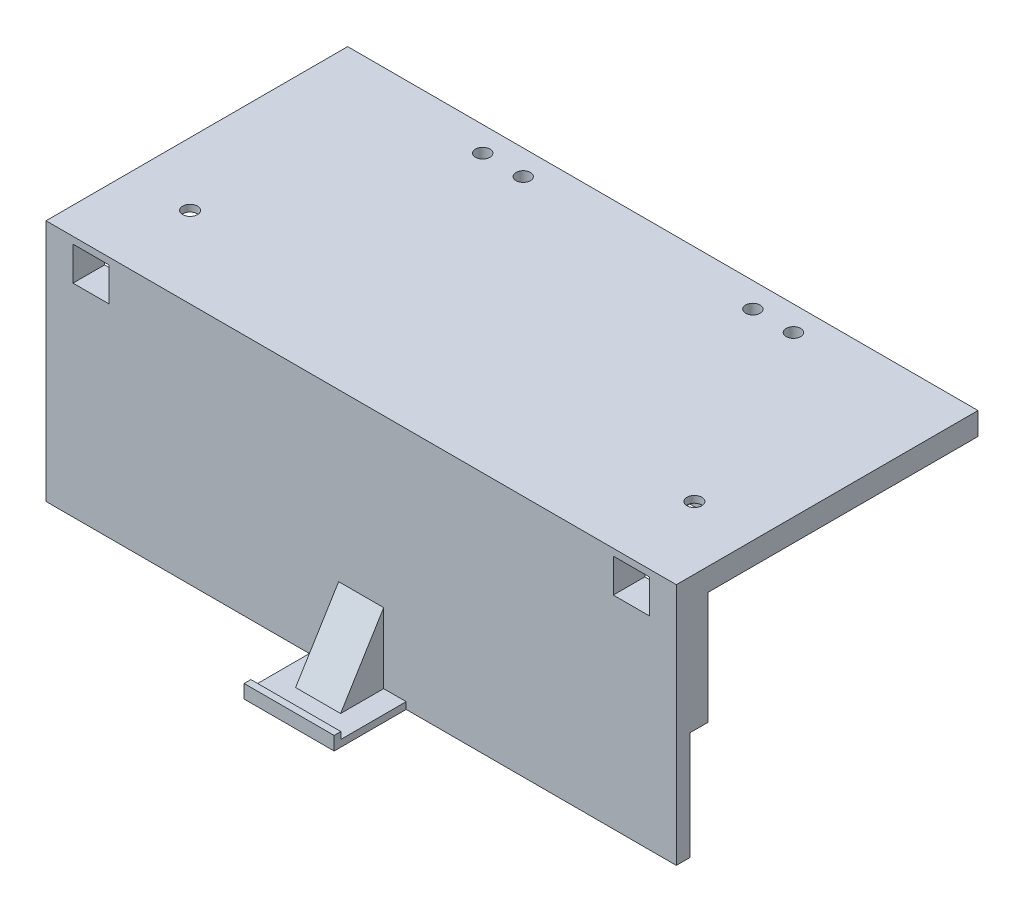
SolidWorks part; units mm, degrees
ref_plane "前视基准面" through (0, 0, 0) normal (0, 0, 1) x (1, 0, 0)
ref_plane "上视基准面" through (0, 0, 0) normal (0, 1, 0) x (1, 0, 0)
ref_plane "右视基准面" through (0, 0, 0) normal (1, 0, 0) x (0, 0, -1)
sketch "草图1" plane through (0, 0, 0) normal (1, 0, 0) x (0, 0, -1)
  line L0 (-15, 27) -> (15, 27)
  line L1 (-15, 27) -> (15, 27) construction
  line L2 (-15, 27) -> (-15, -27) construction
  line L3 (-15, -27) -> (15, -27) construction
  line L4 (15, 27) -> (15, -27) construction
  line L5 (-15, 27) -> (15, -27) construction
  line L6 (-15, -27) -> (15, 27) construction
  line L7 (15, 27) -> (-15, 27) construction
  line L8 (15, 27) -> (15, 17) construction
  line L9 (15, 17) -> (-15, 17) construction
  line L10 (-15, 27) -> (-15, 17) construction
  line L11 (15, 27) -> (-15, 17) construction
  line L12 (15, 17) -> (-15, 27) construction
  line L13 (-15, 17) -> (-12, 17) construction
  line L14 (-15, 17) -> (-15, -27) construction
  line L15 (-15, -27) -> (-12, -27) construction
  line L16 (-12, 17) -> (-12, -27) construction
  line L17 (-15, 17) -> (-12, -27) construction
  line L18 (-15, -27) -> (-12, 17) construction
  line L19 (15, 17) -> (-8, 17) construction
  line L20 (15, 17) -> (15, 27) construction
  line L21 (15, 27) -> (-8, 27) construction
  line L22 (-8, 17) -> (-8, 27) construction
  line L23 (15, 17) -> (-8, 27) construction
  line L24 (15, 27) -> (-8, 17) construction
  line L25 (15, 27) -> (-8, 27) construction
  line L26 (15, 27) -> (15, 22) construction
  line L27 (15, 22) -> (-8, 22) construction
  line L28 (-8, 27) -> (-8, 22) construction
  line L29 (15, 27) -> (-8, 22) construction
  line L30 (15, 22) -> (-8, 27) construction
  line L31 (15, 27) -> (15, 22)
  line L32 (15, 22) -> (-8, 22)
  line L33 (-8, 22) -> (-8, 17)
  line L36 (-12, -27) -> (-15, -27)
  line L37 (-15, -27) -> (-15, 27)
  line L38 (-8, 17) -> (-8, -3)
  line L39 (-8, 17) -> (-12, 17) construction
  line L40 (-8, 17) -> (-8, -3) construction
  line L41 (-8, -3) -> (-12, -3) construction
  line L42 (-12, 17) -> (-12, -3) construction
  line L43 (-10, -3) -> (-10, 17) construction
  line L44 (-8, 7) -> (-12, 7) construction
  line L45 (-8, -3) -> (-12, -3)
  line L46 (-12, -3) -> (-12, -27)
  point P0 (0, 0)
  point P8 (0, 22)
  point P11 (-13.5, -5)
  point P14 (3.5, 22)
  point P17 (3.5, 24.5)
  point P368 (-10, 7)
  dimension "D1" = 54
  dimension "D2" = 30
  dimension "D3" = 10
  dimension "D4" = 3
  dimension "D5" = 23
  dimension "D6" = 20
extrude "凸台-拉伸1" add sketch "草图1" along normal blind 140
sketch "草图2" plane through (0, 27, 0) normal (0, 1, 0) x (1, 0, 0)
  line L1 (0, -15) -> (140, -15) construction
  line L2 (0, -15) -> (0, 15) construction
  line L3 (0, 15) -> (140, 15) construction
  line L4 (140, -15) -> (140, 15) construction
  line L5 (0, -15) -> (140, 15) construction
  line L6 (0, 15) -> (140, -15) construction
  line L7 (0, -15) -> (140, -15) construction
  line L8 (0, -15) -> (0, 3) construction
  line L9 (0, 3) -> (140, 3) construction
  line L10 (140, -15) -> (140, 3) construction
  line L11 (0, -15) -> (140, 3) construction
  line L12 (0, 3) -> (140, -15) construction
  line L13 (14, 3) -> (126, 3) construction
  line L14 (14, 3) -> (14, -15) construction
  line L15 (14, -15) -> (126, -15) construction
  line L16 (126, 3) -> (126, -15) construction
  line L17 (14, 3) -> (126, -15) construction
  line L18 (14, -15) -> (126, 3) construction
  circle A0 centre (14, 3) radius 1.65
  circle A1 centre (126, 3) radius 1.65
  point P4 (70, 0)
  point P9 (70, -6)
  point P10 (70, -6)
  dimension "D1" = 18
  dimension "D2" = 112
extrude "切除-拉伸1" cut sketch "草图2" against normal up to surface (5 mm away) up to face at (70, 22, -3.5)
sketch "草图3" plane through (0, 0, 15) normal (0, 0, 1) x (1, 0, 0)
  line L1 (0, 27) -> (140, 27) construction
  line L2 (0, 27) -> (0, -27) construction
  line L3 (0, -27) -> (140, -27) construction
  line L4 (140, 27) -> (140, -27) construction
  line L5 (0, 27) -> (140, -27) construction
  line L6 (0, -27) -> (140, 27) construction
  line L7 (14, 27) -> (126, 27) construction
  line L8 (14, 27) -> (14, -27) construction
  line L9 (14, -27) -> (126, -27) construction
  line L10 (126, 27) -> (126, -27) construction
  line L11 (14, 27) -> (126, -27) construction
  line L12 (14, -27) -> (126, 27) construction
  line L13 (6, 27) -> (134, 27) construction
  line L14 (6, 27) -> (6, -27) construction
  line L15 (6, -27) -> (134, -27) construction
  line L16 (134, 27) -> (134, -27) construction
  line L17 (6, 27) -> (134, -27) construction
  line L18 (6, -27) -> (134, 27) construction
  line L19 (6, 27) -> (134, 27) construction
  line L20 (6, 27) -> (6, 18) construction
  line L21 (6, 18) -> (134, 18) construction
  line L22 (134, 27) -> (134, 18) construction
  line L23 (6, 27) -> (134, 18) construction
  line L24 (6, 18) -> (134, 27) construction
  line L25 (6, 27) -> (134, 27) construction
  line L26 (6, 27) -> (6, 25.5) construction
  line L27 (6, 25.5) -> (134, 25.5) construction
  line L28 (134, 27) -> (134, 25.5) construction
  line L29 (6, 27) -> (134, 25.5) construction
  line L30 (6, 25.5) -> (134, 27) construction
  line L31 (6, 25.5) -> (14, 25.5)
  line L32 (6, 25.5) -> (6, 18)
  line L33 (6, 18) -> (14, 18)
  line L34 (14, 25.5) -> (14, 18)
  line L35 (6, 25.5) -> (14, 18) construction
  line L36 (6, 18) -> (14, 25.5) construction
  line L37 (134, 18) -> (126, 18)
  line L38 (134, 18) -> (134, 25.5)
  line L39 (134, 25.5) -> (126, 25.5)
  line L40 (126, 18) -> (126, 25.5)
  line L41 (134, 18) -> (126, 25.5) construction
  line L42 (134, 25.5) -> (126, 18) construction
  point P4 (70, 0)
  point P7 (70, 0)
  point P12 (70, 0)
  point P19 (70, 22.5)
  point P22 (70, 26.25)
  point P23 (14, 18)
  point P24 (126, 18)
  point P25 (126, 25.5)
  point P26 (14, 25.5)
  point P29 (10, 21.75)
  point P32 (130, 21.75)
  dimension "D1" = 112
  dimension "D2" = 128
  dimension "D3" = 9
  dimension "D4" = 1.5
extrude "切除-拉伸2" cut sketch "草图3" against normal through all
sketch "草图4" plane through (0, 22, 0) normal (0, -1, 0) x (1, 0, 0)
  line L1 (9, 1) -> (19, 1)
  line L2 (9, 1) -> (9, -7)
  line L3 (9, -7) -> (19, -7)
  line L4 (19, 1) -> (19, -7)
  line L5 (9, 1) -> (19, -7) construction
  line L6 (9, -7) -> (19, 1) construction
  line L7 (121, 1) -> (131, 1)
  line L8 (121, 1) -> (121, -7)
  line L9 (121, -7) -> (131, -7)
  line L10 (131, 1) -> (131, -7)
  line L11 (121, 1) -> (131, -7) construction
  line L12 (121, -7) -> (131, 1) construction
  point P0 (14, -3)
  point P6 (126, -3)
  dimension "D1" = 10
  dimension "D2" = 8
  dimension "D3" = 10
  dimension "D4" = 8
extrude "切除-拉伸3" cut sketch "草图4" against normal up to surface (3.5 mm away) up to face at (11.0583, 25.5, -1)
sketch "草图5" plane through (0, 0, 15) normal (0, 0, 1) x (1, 0, 0)
  line L0 (140, 27) -> (140, -27) construction
  line L1 (0, 27) -> (140, 27) construction
  line L2 (0, 27) -> (0, -27) construction
  line L3 (0, -27) -> (140, -27) construction
  line L4 (140, 27) -> (140, -27) construction
  line L5 (0, 27) -> (140, -27) construction
  line L6 (0, -27) -> (140, 27) construction
  line L8 (60, 27) -> (80, 27) construction
  line L9 (60, 27) -> (60, -27) construction
  line L10 (60, -27) -> (80, -27) construction
  line L11 (80, 27) -> (80, -27) construction
  line L12 (60, 27) -> (80, -27) construction
  line L13 (60, -27) -> (80, 27) construction
  line L14 (60, -27) -> (80, -27)
  line L15 (60, -27) -> (60, -25.5)
  line L16 (60, -25.5) -> (80, -25.5)
  line L17 (80, -27) -> (80, -25.5)
  line L18 (60, -27) -> (80, -25.5) construction
  line L19 (60, -25.5) -> (80, -27) construction
  point P4 (70, 0)
  point P8 (70, 0)
  point P15 (70, -26.25)
  dimension "D1" = 54
  dimension "D2" = 20
  dimension "D3" = 1.5
extrude "凸台-拉伸2" add sketch "草图5" along normal blind 16
sketch "草图6" plane through (80, 0, 0) normal (1, 0, 0) x (0, 0, -1)
  line L1 (-31, -25.5) -> (-29.5, -25.5)
  line L2 (-31, -25.5) -> (-31, -24)
  line L3 (-31, -24) -> (-29.5, -24)
  line L4 (-29.5, -25.5) -> (-29.5, -24)
  line L5 (-31, -25.5) -> (-29.5, -24) construction
  line L6 (-31, -24) -> (-29.5, -25.5) construction
  point P4 (-30.25, -24.75)
  dimension "D1" = 1.5
  dimension "D2" = 1.5
extrude "凸台-拉伸3" add sketch "草图6" against normal up to surface (20 mm away) up to face at (60, -26.25, 23)
ref_plane "基准面1" through (70, 0, 0) normal (-1, 0, 0) x (0, 0, 1)
sketch "草图8" plane through (70, 0, 0) normal (-1, 0, 0) x (0, 0, 1)
  line L0 (15, -9.9149) -> (24.5689, -25.5)
  line L1 (15, 27) -> (15, -27) construction
  line L2 (29.5, -25.5) -> (15, -25.5) construction
rib "筋1" sketch "草图8" sketch "草图8" thickness 10 extrusion direction parallel to sketch draft on no parameters "D1"=10
sketch "草图9" plane through (0, 0, -15) normal (0, 0, -1) x (-1, 0, 0)
  line L1 (-140, 27) -> (0, 27)
  line L2 (-140, 27) -> (-140, 22)
  line L3 (-140, 22) -> (0, 22)
  line L4 (0, 27) -> (0, 22)
  line L5 (-70, 22) -> (-70, 27) construction
  line L6 (-140, 24.5) -> (0, 24.5) construction
  point P152 (-70, 24.5)
extrude "凸台-拉伸4" add sketch "草图9" along normal blind 37
sketch "草图10" plane through (0, 27, 0) normal (0, 1, 0) x (1, 0, 0)
  line L0 (140, 52) -> (140, -15) construction
  line L1 (0, 52) -> (140, 52) construction
  line L2 (0, 52) -> (0, 46.5) construction
  line L3 (0, 46.5) -> (140, 46.5) construction
  line L4 (140, 52) -> (140, 46.5) construction
  line L5 (70, 46.5) -> (70, 52) construction
  line L6 (0, 49.25) -> (140, 49.25) construction
  line L8 (50, 52) -> (90, 52) construction
  line L9 (50, 52) -> (50, 46.5) construction
  line L10 (50, 46.5) -> (90, 46.5) construction
  line L11 (90, 52) -> (90, 46.5) construction
  line L12 (70, 46.5) -> (70, 52) construction
  line L13 (50, 49.25) -> (90, 49.25) construction
  line L14 (50, 52) -> (30, 52) construction
  line L15 (50, 52) -> (50, 46.5) construction
  line L16 (50, 46.5) -> (30, 46.5) construction
  line L17 (30, 52) -> (30, 46.5) construction
  line L18 (40, 46.5) -> (40, 52) construction
  line L19 (50, 49.25) -> (30, 49.25) construction
  line L20 (35.5, 52) -> (44.5, 52) construction
  line L21 (35.5, 52) -> (35.5, 46.5) construction
  line L22 (35.5, 46.5) -> (44.5, 46.5) construction
  line L23 (44.5, 52) -> (44.5, 46.5) construction
  line L24 (40, 46.5) -> (40, 52) construction
  line L25 (35.5, 49.25) -> (44.5, 49.25) construction
  circle A0 centre (35.5, 46.5) radius 1.6
  circle A1 centre (44.5, 46.5) radius 1.6
  circle A2 centre (95.5, 46.5) radius 1.6
  circle A3 centre (104.5, 46.5) radius 1.6
  point P6 (70, 49.25)
  point P13 (40, 49.25)
  point P68 (40, 49.25)
  point P132 (70, 49.25)
  dimension "D1" = 5.5
  dimension "D2" = 40
  dimension "D3" = 20
  dimension "D4" = 9
extrude "切除-拉伸4" cut sketch "草图10" against normal up to surface (5 mm away) up to face at (70, 22, -7)
